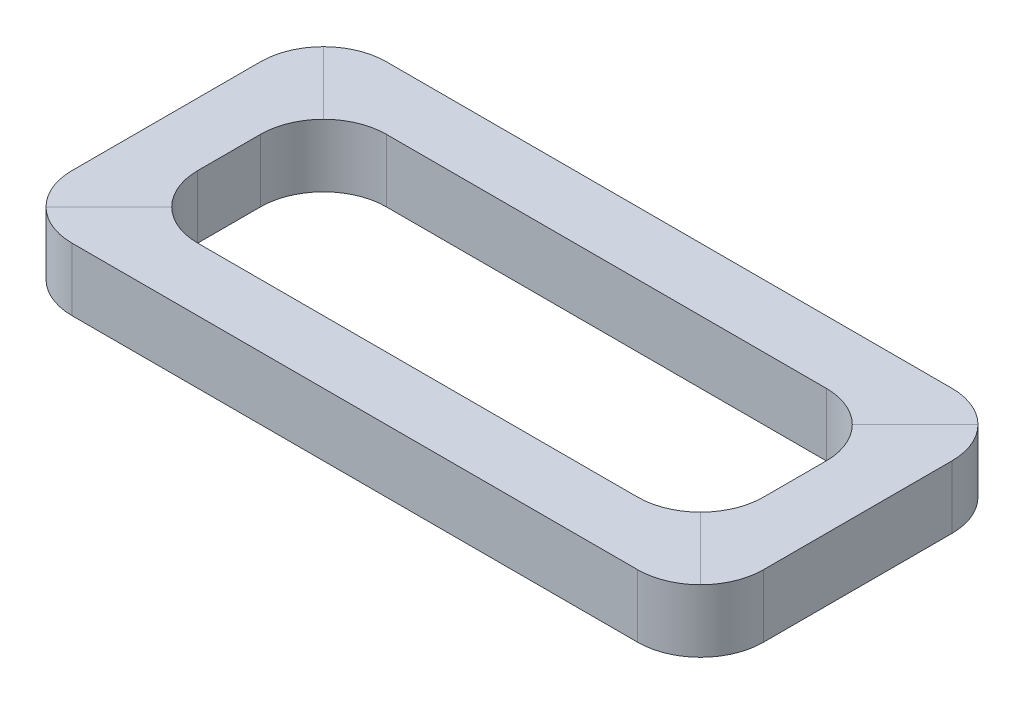
SolidWorks part; units mm, degrees
ref_plane "Front Plane" through (0, 0, 0) normal (0, 0, 1) x (1, 0, 0)
ref_plane "Top Plane" through (0, 0, 0) normal (0, 1, 0) x (1, 0, 0)
ref_plane "Right Plane" through (0, 0, 0) normal (1, 0, 0) x (0, 0, -1)
sketch "Sketch3" plane through (0, 0, 0) normal (1, 0, 0) x (0, 0, -1)
  line L1 (2.5, 2.5) -> (-2.5, 2.5)
  line L2 (2.5, 2.5) -> (2.5, -2.5)
  line L3 (2.5, -2.5) -> (-2.5, -2.5)
  line L4 (-2.5, 2.5) -> (-2.5, -2.5)
  line L5 (2.5, 2.5) -> (-2.5, -2.5) construction
  line L6 (2.5, -2.5) -> (-2.5, 2.5) construction
  point P0 (0, 0)
  dimension "D1" = 5
  dimension "D2" = 5
sketch "Sketch4" plane through (0, 0, 0) normal (0, 1, 0) x (1, 0, 0)
  line L0 (0, 0) -> (50, 0)
  line L1 (50, 0) -> (50, -20)
  line L2 (50, -20) -> (0, -20)
  line L3 (0, -20) -> (0, 0)
  dimension "D1" = 50
  dimension "D2" = 20
sweep "Sweep2" add profiles "Sketch3" path "Sketch4"
fillet "Fillet1" radius 5 8 edges at (-2.5, 0, -2.5) (52.5, 0, -2.5) (-2.5, 0, 22.5) (52.5, 0, 22.5) (2.5, 0, 2.5) (2.5, 0, 17.5) (47.5, 0, 17.5) (47.5, 0, 2.5)
